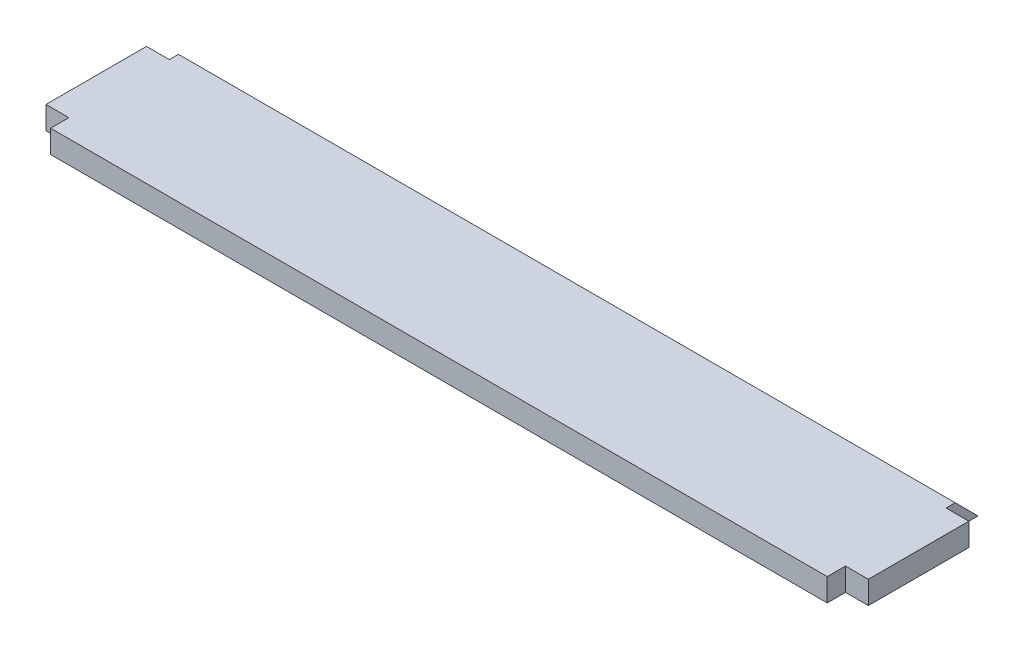
SolidWorks part; units mm, degrees
ref_plane "Front Plane" through (0, 0, 0) normal (0, 0, 1) x (1, 0, 0)
ref_plane "Top Plane" through (0, 0, 0) normal (0, 1, 0) x (1, 0, 0)
ref_plane "Right Plane" through (0, 0, 0) normal (1, 0, 0) x (0, 0, -1)
sketch "Sketch2" plane through (0, 0, 0) normal (0, 1, 0) x (1, 0, 0)
  line L1 (-85, 17.5) -> (85, 17.5)
  line L2 (-85, 17.5) -> (-85, -17.5)
  line L3 (-85, -17.5) -> (85, -17.5)
  line L4 (85, 17.5) -> (85, -17.5)
  line L5 (-85, 17.5) -> (85, -17.5) construction
  line L6 (-85, -17.5) -> (85, 17.5) construction
  point P0 (0, 0)
  dimension "D1" = 170
  dimension "D2" = 35
extrude "Boss-Extrude1" add sketch "Sketch2" along normal blind 5
sketch "Sketch4" plane through (-85, 0, 0) normal (-1, 0, 0) x (0, 0, 1)
  line L0 (-17.5, 0) -> (-12.5, 5)
  line L1 (-17.5, 5) -> (17.5, 5) construction
  line L2 (-17.5, 0) -> (12.5, 30) construction
  line L3 (-12.5, 5) -> (-17.5, 5)
  line L4 (-17.5, 5) -> (-17.5, 0) construction
  line L5 (-17.5, 5) -> (-17.5, 0)
extrude "Cut-Extrude1" cut sketch "Sketch4" against normal blind 200
sketch "Sketch5" plane through (-85, 0, 0) normal (-1, 0, 0) x (0, 0, 1)
  line L0 (-12.5, 5) -> (17.5, 5) construction
  line L1 (-8.5, 0) -> (13.5, 0)
  line L2 (-8.5, 0) -> (-8.5, 5)
  line L3 (-8.5, 5) -> (13.5, 5)
  line L4 (13.5, 0) -> (13.5, 5)
  line L5 (-8.5, 0) -> (13.5, 5) construction
  line L6 (-8.5, 5) -> (13.5, 0) construction
  line L7 (-17.5, 0) -> (17.5, 0) construction
  line L8 (17.5, 5) -> (17.5, 0) construction
  point P0 (2.5, 2.5)
  dimension "D1" = 22
  dimension "D2" = 4
extrude "Boss-Extrude2" add sketch "Sketch5" along normal blind 5
sketch "Sketch6" plane through (85, 0, 0) normal (1, 0, 0) x (0, 0, -1)
  line L0 (-17.5, 5) -> (12.5, 5) construction
  line L1 (8.5, 5) -> (-13.5, 5)
  line L2 (8.5, 5) -> (8.5, 0)
  line L3 (8.5, 0) -> (-13.5, 0)
  line L4 (-13.5, 5) -> (-13.5, 0)
  line L5 (-17.5, 0) -> (17.5, 0) construction
  line L6 (-17.5, 5) -> (-17.5, 0) construction
  dimension "D1" = 22
  dimension "D2" = 4
extrude "Boss-Extrude3" add sketch "Sketch6" along normal blind 5
sketch "Sketch7" plane through (85, 0, 0) normal (1, 0, 0) x (0, 0, -1)
  line L0 (12.5, 5) -> (10.5, 5)
  line L1 (8.5, 5) -> (12.5, 5) construction
  line L2 (10.5, 5) -> (15.5, 0)
  line L3 (8.5, 0) -> (17.5, 0) construction
  line L4 (15.5, 0) -> (17.5, 0)
  line L5 (17.5, 0) -> (12.5, 5)
extrude "Cut-Extrude2" cut sketch "Sketch7" against normal blind 563
